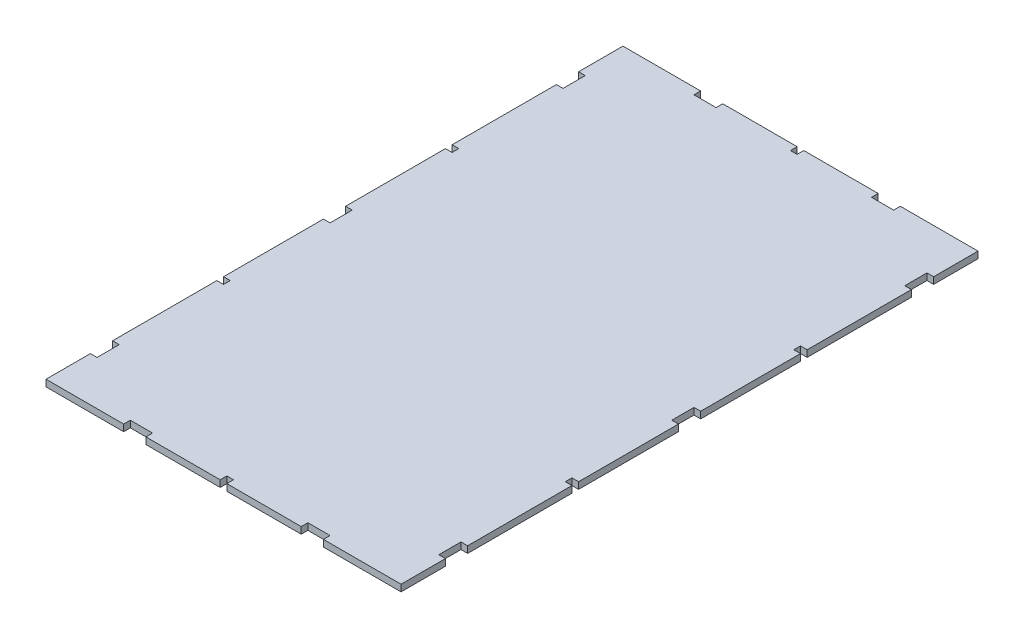
SolidWorks part; units mm, degrees
ref_plane "Front Plane" through (0, 0, 0) normal (0, 0, 1) x (1, 0, 0)
ref_plane "Top Plane" through (0, 0, 0) normal (0, 1, 0) x (1, 0, 0)
ref_plane "Right Plane" through (0, 0, 0) normal (1, 0, 0) x (0, 0, -1)
sketch "Sketch1" plane through (0, 0, 0) normal (0, 1, 0) x (1, 0, 0)
  line L1 (-80, 110) -> (80, 110)
  line L2 (-80, 110) -> (-80, -150)
  line L3 (-80, -150) -> (80, -150)
  line L4 (80, 110) -> (80, -150)
  dimension "D1" = 160
  dimension "D2" = 150
  dimension "D3" = 80
  dimension "D4" = 110
extrude "Boss-Extrude1" add sketch "Sketch1" along normal blind 3
sketch "Sketch7" plane through (0, 3, 0) normal (0, 1, 0) x (1, 0, 0)
  line L0 (80, 110) -> (-80, 110) construction
  line L1 (1.5, 107) -> (-1.5, 107)
  line L2 (1.5, 107) -> (1.5, 110)
  line L3 (1.5, 110) -> (-1.5, 110)
  line L4 (-1.5, 107) -> (-1.5, 110)
  line L5 (0, 122.6308) -> (0, 84.273) construction
  line L6 (45, 107) -> (45, 110)
  line L7 (-35, 107) -> (-45, 107)
  line L8 (-35, 107) -> (-35, 110)
  line L9 (-35, 110) -> (-45, 110)
  line L10 (-45, 107) -> (-45, 110)
  line L11 (35, 110) -> (45, 110)
  line L12 (35, 107) -> (35, 110)
  line L13 (35, 107) -> (45, 107)
  line L14 (-80, -20) -> (80, -20) construction
  line L15 (-80, 110) -> (-80, -150) construction
  line L16 (80, -150) -> (80, 110) construction
  line L17 (35, -147) -> (45, -147)
  line L18 (35, -147) -> (35, -150)
  line L19 (35, -150) -> (45, -150)
  line L20 (-45, -147) -> (-45, -150)
  line L21 (-35, -150) -> (-45, -150)
  line L22 (-35, -147) -> (-35, -150)
  line L23 (-35, -147) -> (-45, -147)
  line L24 (45, -147) -> (45, -150)
  line L25 (-1.5, -147) -> (-1.5, -150)
  line L26 (1.5, -150) -> (-1.5, -150)
  line L27 (1.5, -147) -> (1.5, -150)
  line L28 (1.5, -147) -> (-1.5, -147)
  line L29 (-77, -130) -> (-77, -120)
  line L30 (-80, -15) -> (-77, -15)
  line L31 (-80, -15) -> (-80, -25)
  line L32 (-80, -25) -> (-77, -25)
  line L33 (-77, -15) -> (-77, -25)
  line L34 (-80, 90) -> (-77, 90)
  line L35 (-80, 90) -> (-80, 80)
  line L36 (-80, 80) -> (-77, 80)
  line L37 (-77, 90) -> (-77, 80)
  line L38 (-80, -120) -> (-77, -120)
  line L39 (-80, -130) -> (-80, -120)
  line L40 (-80, -130) -> (-77, -130)
  line L41 (-77, -73) -> (-77, -70)
  line L42 (-80, 33) -> (-77, 33)
  line L43 (-80, 33) -> (-80, 30)
  line L44 (-80, 30) -> (-77, 30)
  line L45 (-77, 33) -> (-77, 30)
  line L46 (-80, -70) -> (-77, -70)
  line L47 (-80, -73) -> (-80, -70)
  line L48 (-80, -73) -> (-77, -73)
  line L49 (80, -130) -> (77, -130)
  line L50 (80, -130) -> (80, -120)
  line L51 (80, -120) -> (77, -120)
  line L52 (77, -130) -> (77, -120)
  line L53 (80, -73) -> (77, -73)
  line L54 (80, -73) -> (80, -70)
  line L55 (80, -70) -> (77, -70)
  line L56 (77, -73) -> (77, -70)
  line L57 (77, -15) -> (77, -25)
  line L58 (80, -25) -> (77, -25)
  line L59 (80, -15) -> (80, -25)
  line L60 (80, -15) -> (77, -15)
  line L61 (77, 33) -> (77, 30)
  line L62 (80, 30) -> (77, 30)
  line L63 (80, 33) -> (80, 30)
  line L64 (80, 33) -> (77, 33)
  line L65 (77, 90) -> (77, 80)
  line L66 (80, 80) -> (77, 80)
  line L67 (80, 90) -> (80, 80)
  line L68 (80, 90) -> (77, 90)
  dimension "D1" = 3
  dimension "D2" = 3
  dimension "D3" = 1.5
  dimension "D4" = 10
  dimension "D5" = 3
  dimension "D6" = 45
  dimension "D7" = 5
  dimension "D8" = 10
  dimension "D9" = 3
  dimension "D10" = 3
  dimension "D11" = 10
  dimension "D12" = 100
  dimension "D13" = 3
  dimension "D14" = 3
  dimension "D15" = 50
extrude "Cut-Extrude2" cut sketch "Sketch7" against normal through all
